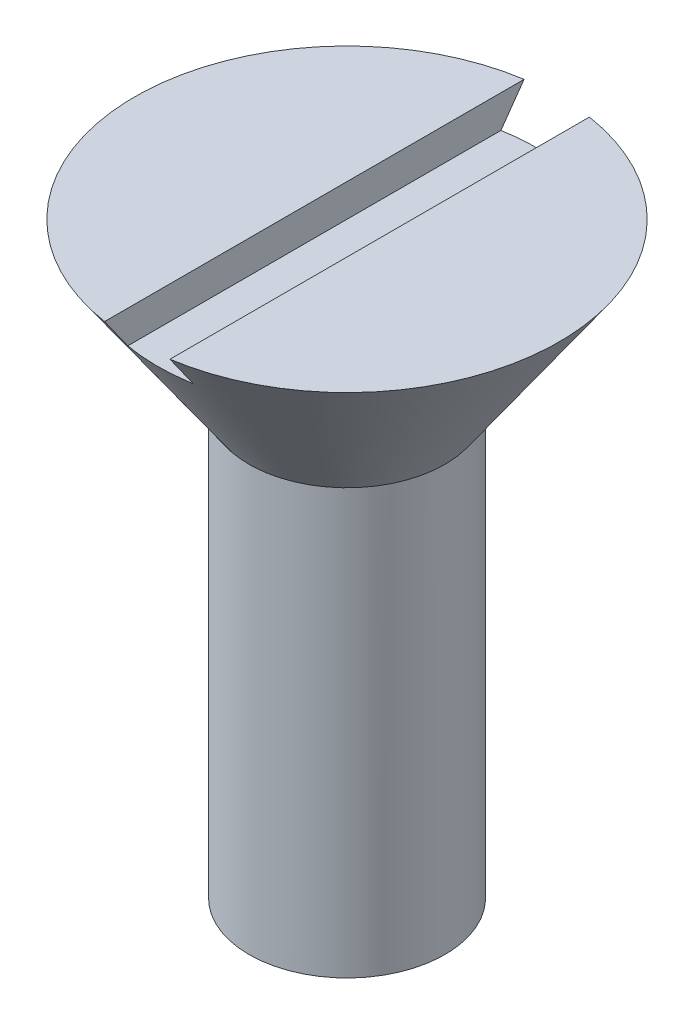
SolidWorks part; units mm, degrees
ref_plane "Front Plane" through (0, 0, 0) normal (0, 0, 1) x (1, 0, 0)
ref_plane "Top Plane" through (0, 0, 0) normal (0, 1, 0) x (1, 0, 0)
ref_plane "Right Plane" through (0, 0, 0) normal (1, 0, 0) x (0, 0, -1)
sketch "Sketch1" plane through (0, 0, 0) normal (0, 0, 1) x (1, 0, 0)
  line L4 (3, -5) -> (3, -18)
  line L7 (3, -18) -> (0, -19.7321)
  line L8 (0, -19.7321) -> (12.4657, -19.7321) construction
  line L11 (0, 0) -> (0, -19.7321)
  line L12 (0, 0) -> (6.5, 0)
  line L13 (6.5, 0) -> (3, -5)
  line L14 (0, 0) -> (0, 5.3177) construction
  dimension "D1" = 30
  dimension "D2" = 13
  dimension "D3" = 6
  dimension "D4" = 5
  dimension "D5" = 13
revolve "Revolve5" add sketch "Sketch1" angle 360 about L14
sketch "Sketch2" plane through (0, 0, 0) normal (0, 1, 0) x (1, 0, 0)
  line L0 (0, 6.5) -> (0, -6.5)
  line L1 (-1, 6.5) -> (-1, -6.5)
  line L2 (1, 6.5) -> (1, -6.5)
  line L3 (-1, -6.5) -> (1, -6.5)
  line L4 (1, 6.5) -> (-1, 6.5)
  circle A0 centre (0, 0) radius 6.5 construction
  circle M2 centre (0, 0) radius 6.5
  dimension "D1" = 1
  dimension "D2" = 1
extrude "Cut-Extrude1" cut sketch "Sketch2" against normal blind 1 contours L1 L0 M2 | L2 L0 M2
